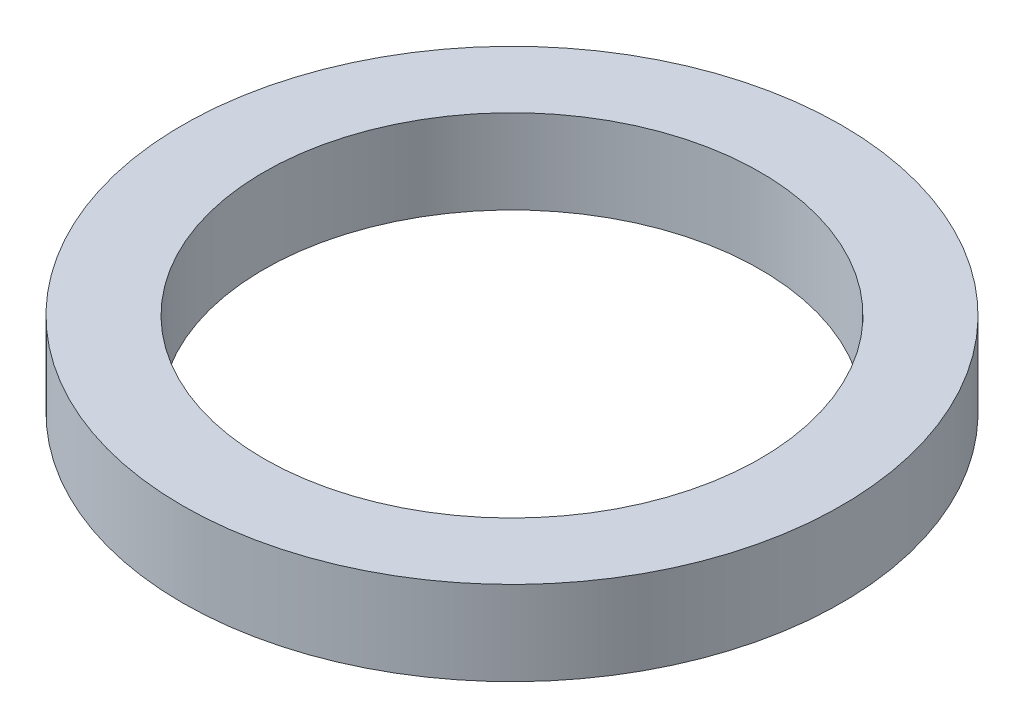
SolidWorks part; units mm, degrees
ref_plane "Front Plane" through (0, 0, 0) normal (0, 0, 1) x (1, 0, 0)
ref_plane "Top Plane" through (0, 0, 0) normal (0, 1, 0) x (1, 0, 0)
ref_plane "Right Plane" through (0, 0, 0) normal (1, 0, 0) x (0, 0, -1)
sketch "Sketch1" plane through (0, 0, 0) normal (0, 1, 0) x (1, 0, 0)
  circle A0 centre (0, 0) radius 29
  circle A1 centre (0, 0) radius 38.505
  dimension "D1" = 58
  dimension "D2" = 77.01
extrude "Boss-Extrude1" add sketch "Sketch1" along normal mid plane 9.84
equation "\"Nr\"= \"Ns\" + 2 * \"Np\"'num teeth"
equation "\"module\"= 0.8"
equation "\"pressure_angle\"= 20deg"
equation "\"h_a\"= 1 * \"module\"'addendum"
equation "\"h_f\"= 1.25 * \"module\"'dedendum"
equation "\"clr_tip_root\"= \"h_f\" - \"h_a\"'clearance of gear tooth tip and root"
equation "\"dp_r\"= \"module\" * \"Nr\"'PCD"
equation "\"db_r\"= \"dp_r\" * cos ( \"pressure_angle\" )'base CD"
equation "\"fw_r\"= 11.5mm'face width"
equation "\"alpha_r\"= sqr ( \"dp_r\" ^ 2 - \"db_r\" ^ 2 ) / \"db_r\" * 180 / pi - \"pressure_angle\""
equation "\"beta_r\"= ( 360 / ( 4 * \"Nr\" ) + \"alpha_r\" ) * 2"
equation "\"bearing_ID\"= \"module\" * ( \"Ns\" + \"Np\" ) + 10"
equation "\"bearing_OD\"= 1.18 * \"bearing_ID\" + 8.57"
equation "\"bearing_height\"= 0.09 * \"bearing_ID\" + 4.62"
equation "\"clearance_planet\"=1.5"
equation "\"case_dist\"= \"sec_carrier_thickness\" + \"clearance_planet\" + \"sun_coupler_hub_thickness\" - \"case_mounting_surface_height\""
equation "\"Motor_case_OD_max\"= \"case_mounting_PCD\" + \"case_mounting_hole_allen_socket_dia\" + \"clearance_case_mount_holes_shell_thickness\" * 2"
equation "\"case_mounting_PCD\"= \"motor_case_OD_base\" + \"case_mounting_hole_shift\" * 2"
equation "\"bearing mount thickness\"= IIF((\"bearing_OD\" + \"output_mounting_hole_dia\" * 4) > (\"Nr\" * \"module\" + 2 * \"h_b\"), \"output_mounting_hole_dia\" * 2, ((\"Nr\" * \"module\" + 2 * \"h_b\" - (\"bearing_OD\" + \"output_mounting_hole_dia\" * 4)) / 2) + \"output_mounting_hole_dia\" * 2 + \"standard_clearance_1_5mm\")"
equation "\"case_mounting_hole_dia\"=3"
equation "\"output_mounting_PCD\"= \"bearing_OD\" + \"bearing mount thickness\""
equation "\"output_mounting_hole_dia\"= 4"
equation "\"clearance_case_mount_holes_shell_thickness\"= 1"
equation "\"motor_case_OD_base\"= \"motor_OD\" + \"clearance_motor_and_case\" * 2 + \"Motor_case_thickness\" * 2"
equation "\"sec_carrier_thickness\"= 5"
equation "\"sun_coupler_hub_thickness\"= 4"
equation "\"clearance_sun_coupler_sec_carrier\"= 1.5"
equation "\"clearance_motor_and_case\" = IIF(\"ring_OD\" < \"motor_OD\", 5, (\"ring_OD\" - \"motor_OD\")/2 + 5)"
equation "\"motor_OD\"= 88.6"
equation "\"Motor_case_thickness\"= 2.5"
equation "\"Motor_case_ID\"= \"motor_OD\" + \"clearance_motor_and_case\" * 2"
equation "\"case_mounting_hole_shift\"= \"case_mounting_hole_dia\" / 2 - 0.5"
equation "\"output_mounting_nut_wrench_size\"= 7"
equation "\"output_mounting_nut_thickness\"= 3.2"
equation "\"case_mounting_hole_allen_socket_dia\"= 5.5"
equation "\"output_mounting_nut_depth\"= 3"
equation "\"case_mounting_bolt_depth\"= 4.5"
equation "\"Ns\"= 20"
equation "\"Np\"= 40"
equation "\"ring_radial_thickness\"= 5"
equation "\"ring_OD\"= \"Nr\" * \"module\" + \"ring_radial_thickness\" * 2"
equation "\"ring_to_chamfer_clearance\"= 2"
equation "\"Motor_case_OD_base_to_chamfer\"=5"
equation "\"pattern_offset_from_motor_case_OD_base\"= 3"
equation "\"pattern_bulge_dia\"= 3"
equation "\"pattern_num_bulge\"= 18"
equation "\"pattern_depth\"= 2"
equation "\"motor_height\"= 43"
equation "\"case_mounting_wrench_size\"= 5.5"
equation "\"case_mounting_nut_clearance\"= 2"
equation "\"base_plate_thickness\"= 4"
equation "\"case_mounting_nut_thickness\"= 2.4"
equation "\"case_mounting_surface_height\"= 4"
equation "\"motor_mount_hole_PCD\"= 32"
equation "\"motor_mount_hole_dia\"= 4"
equation "\"motor_mount_hole_num\"= 4"
equation "\"central_hole_offset_from_motor_mount_PCD\"= 5"
equation "\"wire_slot_dist_from_center\"= 30"
equation "\"wire_slot_length\"= 10"
equation "\"wire_slot_radius\"= 4"
equation "\"driver_upper_holes_dist_from_center\"= 23"
equation "\"driver_lower_holes_dist_from_center\"= 15"
equation "\"driver_side_holes_dist_from_center\"= 20"
equation "\"driver_mount_holes_dia\"= 2.5"
equation "\"driver_mount_inserts_OD\"= 3.5"
equation "\"driver_mount_thickness\"= 1.5"
equation "\"driver_mount_height\"= 4"
equation "\"air_flow_hole_offset\"= 3"
equation "\"num_planet\"= 3"
equation "\"planet_pin_bolt_dia\"= 5"
equation "\"planet_pin_socket_head_dia\"= 8.5"
equation "\"carrier_PCD\"= ( \"Np\" + \"Ns\" ) * \"module\""
equation "\"planet_shaft_dia\"= 8"
equation "\"fw_p\"= \"fw_r\""
equation "\"planet_shaft_step_offset\"= 1"
equation "\"carrier_trapezoidal_support_sun_offset\"= 5"
equation "\"carrier_trapezoidal_support_hole_PCD_offset_bearing_ID\"= 4"
equation "\"carrier_trapezoidal_support_hole_dia\"= 3"
equation "\"carrier_trapezoidal_support_hole_socket_head_dia\"= 5.5"
equation "\"carrier_bearing_step_width\"= 1.5"
equation "\"standard_clearance_1_5mm\"=1.5"
equation "\"standard_fillet_1_5mm\"= 1.5"
equation "\"sun_shaft_bearing_OD\"= 16"
equation "\"sun_shaft_bearing_width\"= 4"
equation "\"standard_bearing_insertion_chamfer\"= 0.5"
equation "\"D1@Sketch1\"=\"bearing_ID\""
equation "\"D2@Sketch1\"=\"bearing_OD\""
equation "\"D1@Boss-Extrude1\"=\"bearing_height\""
equation "\"D7@Sketch2\"=\"carrier_trapezoidal_support_hole_dia\""
equation "\"D5@Sketch2\"= 360 / ( 4 * \"Ns\" ) - \"alpha_s\""
equation "\"D3@Sketch2\"=\"dp_s\"- 2*\"h_b\""
equation "\"D9@Sketch2\"=\"carrier_trapezoidal_support_sun_offset\""
equation "\"carrier_trapezoidal_support_hole_wrench_size\"= 5.5"
equation "\"planet_pin_bolt_wrench_size\"= 8"
equation "\"pressure angle\"= 20deg"
equation "\"motor_output_hole_PCD\"= 23"
equation "\"motor_output_hole_dia\"= 4"
equation "\"motor_output_hole_num\"= 4"
equation "\"h_b\"= 1.25 * \"module\"'dedendum"
equation "\"dp_s\"= \"module\" * \"Ns\"'PCD"
equation "\"db_s\"= \"dp_s\" * cos ( \"pressure angle\" )'base CD"
equation "\"fw_s_calc\"= 13mm'face width"
equation "\"alpha_s\"= sqr ( \"dp_s\" ^ 2 - \"db_s\" ^ 2 ) / \"db_s\" * 180 / pi - \"pressure angle\""
equation "\"beta_s\"= ( 360 / ( 4 * \"Ns\" ) - \"alpha_s\" ) * 2"
equation "\"dp_p\"= \"module\" * \"Np\"'PCD"
equation "\"db_p\"= \"dp_p\" * cos ( \"pressure angle\" )'base CD"
equation "\"alpha_p\"= sqr ( \"dp_p\" ^ 2 - \"db_p\" ^ 2 ) / \"db_p\" * 180 / pi - \"pressure angle\""
equation "\"beta_p\"= ( 360 / ( 4 * \"Np\" ) - \"alpha_p\" ) * 2"
equation "\"planet_bearing_OD\"= 12"
equation "\"planet_bearing_width\"= 3"
equation "\"planet_bore\"= 10"
equation "\"sun_shaft_bearing_ID\"= 8"
equation "\"sun_hub_dia\"= \"motor_output_hole_PCD\" + \"motor_output_hole_dia\" + \"standard_clearance_1_5mm\" * 4"
equation "\"sun_central_bolt_dia\"= 5"
equation "\"sun_central_bolt_socket_head_dia\"= 8.5"
equation "\"fw_s_used\"= \"fw_p\" + \"clearance_planet\" + \"sec_carrier_thickness\" + \"standard_clearance_1_5mm\""
equation "\"motor_output_hole_CSK_OD\"= 9'8.96 is exact value"
equation "\"motor_output_hole_CSK_head_height\"= 2.5"
equation "\"bearing_retainer_thickness\"= 2"
